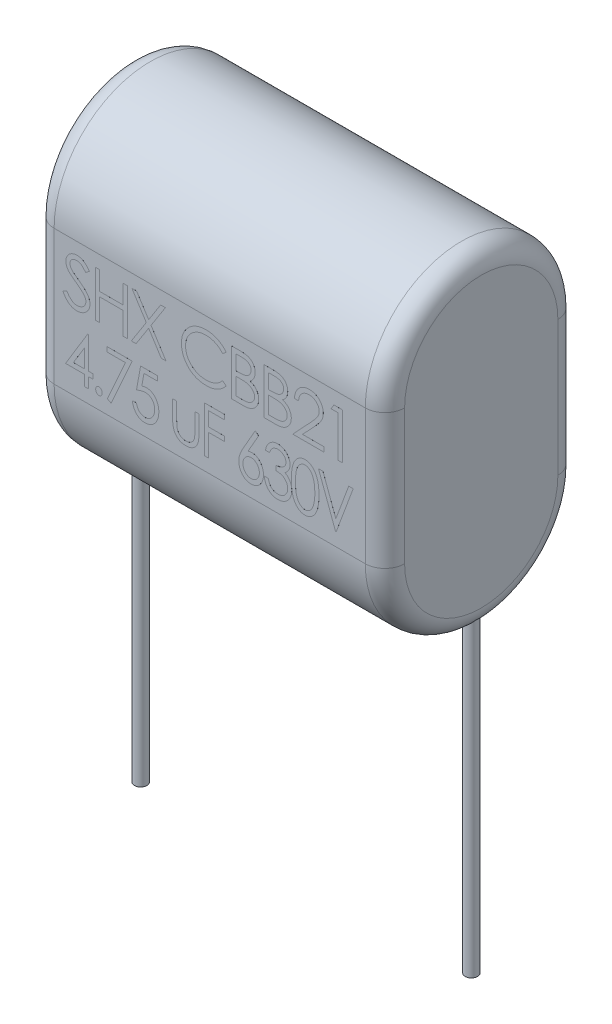
SolidWorks part; units mm, degrees
ref_plane "Front Plane" through (0, 0, 0) normal (0, 0, 1) x (1, 0, 0)
ref_plane "Top Plane" through (0, 0, 0) normal (0, 1, 0) x (1, 0, 0)
ref_plane "Right Plane" through (0, 0, 0) normal (1, 0, 0) x (0, 0, -1)
sketch "Sketch1" plane through (0, 0, 0) normal (1, 0, 0) x (0, 0, -1)
  line L0 (0, 5.15) -> (0, -5.15) construction
  line L1 (7.35, 5.15) -> (7.35, -5.15)
  line L2 (-7.35, 5.15) -> (-7.35, -5.15)
  line L3 (0, 12.5) -> (9.814, 12.5) construction
  line L4 (0, -12.5) -> (9.814, -12.5) construction
  arc A0 (7.35, 5.15) -> (-7.35, 5.15) centre (0, 5.15) ccw
  arc A1 (-7.35, -5.15) -> (7.35, -5.15) centre (0, -5.15) ccw
  point P3 (0, 0)
  dimension "D1" = 25
  dimension "D2" = 14.7
extrude "Boss-Extrude1" add sketch "Sketch1" along normal mid plane 26.75
fillet "Fillet1" radius 1.5 8 edges at (-13.375, 0, 7.35) (-13.375, -12.5, 0) (-13.375, 0, -7.35) (-13.375, 12.5, 0) (13.375, 0, -7.35) (13.375, -12.5, 0) (13.375, 0, 7.35) (13.375, 12.5, 0)
sketch "Sketch2" plane through (0, 0, 0) normal (0, 1, 0) x (1, 0, 0)
  line L0 (0, 0) -> (0, 5.286) construction
  line L1 (0, 0) -> (-7.4166, 0) construction
  line L2 (-12.15, 0) -> (-12.15, -1.5103) construction
  circle A0 centre (-12.62, 0) radius 0.47
  circle A1 centre (12.62, 0) radius 0.47
  dimension "D1" = 12.15
  dimension "D2" = 0.94
extrude "Boss-Extrude3" add sketch "Sketch2" against normal blind 35.5
sketch "Sketch3" plane through (0, 0, 0) normal (0, 0, 1) x (1, 0, 0)
  line L0 (-11.875, 0.65) -> (11.875, 0.65) construction
  line L1 (-11.875, 5.15) -> (-11.875, -5.15) construction
  line L2 (11.875, -5.15) -> (11.875, 5.15) construction
  line L3 (-11.875, -4.15) -> (11.875, -4.15) construction
  line L4 (11.875, 5.15) -> (-11.875, 5.15) construction
  text T0 "SHX CBB21" font "Century Gothic" height 3.5
  text T1 "4.75 uF 630V" font "Century Gothic" height 3.5
  dimension "D1" = 4.5
  dimension "D2" = 4.8
extrude "Boss-Extrude4" add sketch "Sketch3" along normal blind 0.001 from surface at 7.35 starting at face at (0, 0, 7.35)
